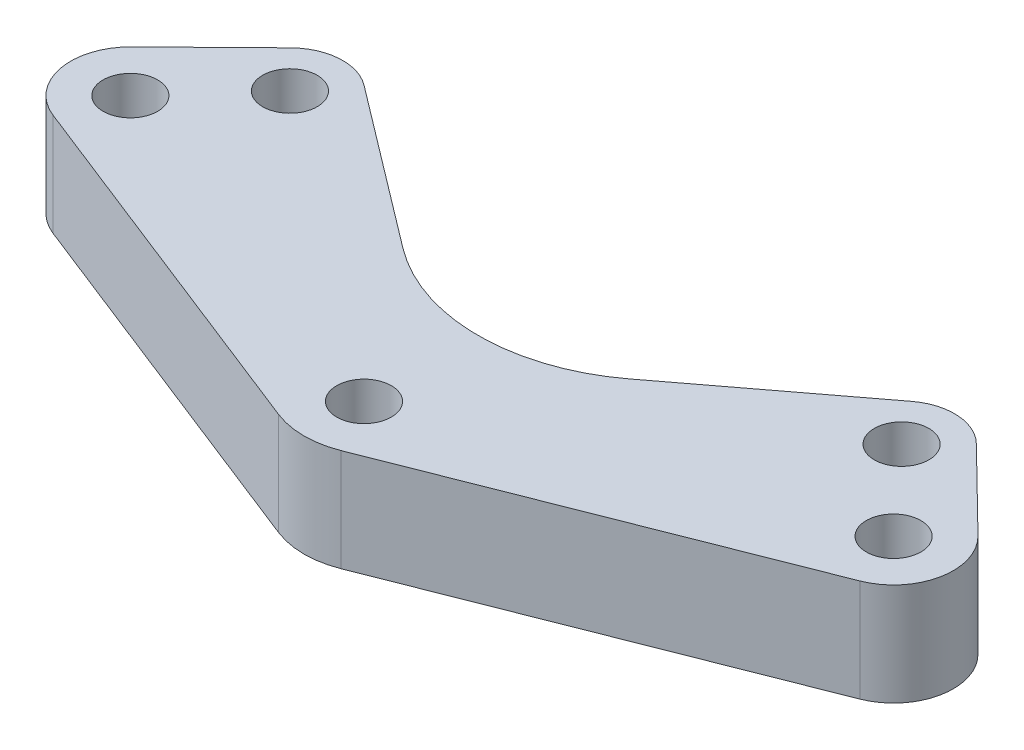
SolidWorks part; units mm, degrees
material "MDF"
ref_plane "Plano frontal" through (0, 0, 0) normal (0, 0, 1) x (1, 0, 0)
ref_plane "Plano superior" through (0, 0, 0) normal (0, 1, 0) x (1, 0, 0)
ref_plane "Plano direito" through (0, 0, 0) normal (1, 0, 0) x (0, 0, -1)
ref_plane "Plano1" through (0, -6, 0) normal (0, -1, 0) x (1, 0, 0)
sketch "Esboço1" plane through (0, -6, 0) normal (0, -1, 0) x (1, 0, 0)
  line L0 (23.6582, -5.4198) -> (1.8308, 3.1692)
  line L1 (-1.8308, 3.1692) -> (-23.6582, -5.4198)
  line L2 (-24.8257, -11.1771) -> (-20.1015, -15.8044)
  line L3 (-16.06, -16.0604) -> (-6.6439, -8.9246)
  line L4 (6.6439, -8.9246) -> (16.06, -16.0604)
  line L5 (20.1015, -15.8044) -> (24.8257, -11.1771)
  line L6 (0, 0) -> (-22.3767, -8.6767) construction
  line L7 (0, 0) -> (22.3767, -8.6767) construction
  line L8 (-22.3767, -8.6767) -> (22.3767, -8.6767) construction
  line L9 (-17.9323, -13.5898) -> (17.9323, -13.5898) construction
  line L10 (17.9323, -13.5898) -> (0, 0) construction
  line L11 (0, 0) -> (-17.9323, -13.5898) construction
  arc A0 (1.8308, 3.1692) -> (-1.8308, 3.1692) centre (0, -1.4835) ccw
  arc A1 (-23.6582, -5.4198) -> (-24.8257, -11.1771) centre (-22.3767, -8.6767) ccw
  arc A2 (-20.1015, -15.8044) -> (-16.06, -16.0604) centre (-17.9323, -13.5898) ccw
  arc A3 (-6.6439, -8.9246) -> (6.6439, -8.9246) centre (0, -17.6915) cw
  arc A4 (16.06, -16.0604) -> (20.1015, -15.8044) centre (17.9323, -13.5898) ccw
  arc A5 (24.8257, -11.1771) -> (23.6582, -5.4198) centre (22.3767, -8.6767) ccw
  circle A6 centre (-17.9323, -13.5898) radius 1.6
  circle A7 centre (0, 0) radius 1.6
  circle A8 centre (17.9323, -13.5898) radius 1.6
  circle A9 centre (-22.3767, -8.6767) radius 1.6
  circle A10 centre (22.3767, -8.6767) radius 1.6
  point P24 (0, -13.5898)
  point P25 (0, -8.6767)
  dimension "D1" = 3.2
  dimension "D2" = 24
  dimension "D4" = 3.5
  dimension "D9" = 11
  dimension "D12" = 3.5
  dimension "D13" = 3.6195
  dimension "D15" = 5
  dimension "D3" = 3.6195
  dimension "D5" = 137.612
  dimension "D6" = 105.688
  dimension "D7" = 22.5
  dimension "D8" = 3.1
  dimension "D11" = 17.6915
  dimension "D14" = 3.1
extrude "Ressalto-extrusão1" add sketch "Esboço1" against normal blind 6
